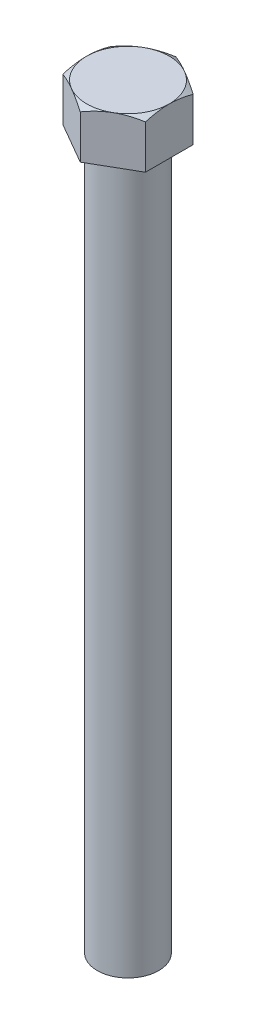
SolidWorks part; units mm, degrees
ref_plane "Front Plane" through (0, 0, 0) normal (0, 0, 1) x (1, 0, 0)
ref_plane "Top Plane" through (0, 0, 0) normal (0, 1, 0) x (1, 0, 0)
ref_plane "Right Plane" through (0, 0, 0) normal (1, 0, 0) x (0, 0, -1)
sketch "Sketch1" plane through (0, 0, 0) normal (0, 1, 0) x (1, 0, 0)
  line L1 (0, 5.1326) -> (-4.445, 2.5663)
  line L2 (-4.445, 2.5663) -> (-4.445, -2.5663)
  line L3 (-4.445, -2.5663) -> (0, -5.1326)
  line L4 (0, -5.1326) -> (4.445, -2.5663)
  line L5 (4.445, -2.5663) -> (4.445, 2.5663)
  line L6 (4.445, 2.5663) -> (0, 5.1326)
  circle A0 centre (0, 0) radius 4.445 construction
  point P1 (0, 0)
  point P10 (0, 0)
  point P11 (0, 0)
  point P12 (0, 0)
  dimension "D1" = 8.89
extrude "Boss-Extrude1" add sketch "Sketch1" along normal mid plane 5.08
sketch "Sketch2" plane through (0, 2.54, 0) normal (0, 1, 0) x (1, 0, 0)
  circle A0 centre (0, 0) radius 4.445
extrude "Cut-Extrude1" cut sketch "Sketch2" against normal blind 5.08 draft 60 flip side to cut
sketch "Sketch3" plane through (0, -2.54, 0) normal (0, -1, 0) x (-1, 0, 0)
  circle A0 centre (0, 0) radius 3.302
  dimension "D1" = 6.604
extrude "Boss-Extrude2" add sketch "Sketch3" along normal blind 76.2
